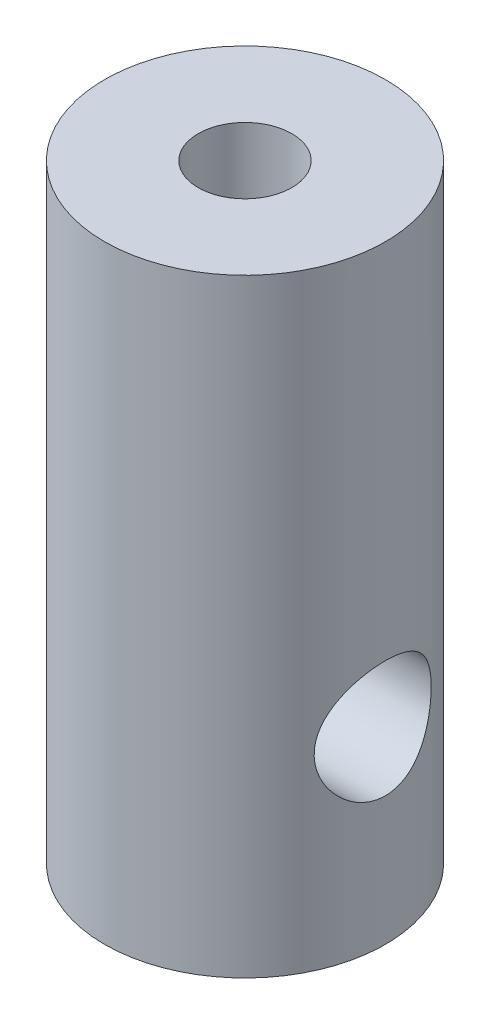
SolidWorks part; units mm, degrees
material "Alliage 1060"
ref_plane "Plan de face" through (0, 0, 0) normal (0, 0, 1) x (1, 0, 0)
ref_plane "Plan de dessus" through (0, 0, 0) normal (0, 1, 0) x (1, 0, 0)
ref_plane "Plan de droite" through (0, 0, 0) normal (1, 0, 0) x (0, 0, -1)
sketch "Esquisse1" plane through (0, 0, 0) normal (0, 1, 0) x (1, 0, 0)
  circle A0 centre (0, 0) radius 3
  dimension "D1" = 6
extrude "Boss.-Extru.1" add sketch "Esquisse1" along normal blind 13
sketch "Esquisse2" plane through (0, 0, 0) normal (0, -1, 0) x (1, 0, 0)
  circle A0 centre (0, 0) radius 1
  dimension "D1" = 2
extrude "Enlèv. mat.-Extru.1" cut sketch "Esquisse2" against normal through all
sketch "Esquisse3" plane through (0, 13, 0) normal (0, 1, 0) x (1, 0, 0)
  line L1 (-1, -3.0804) -> (1, -3.0804)
  line L2 (-1, -3.0804) -> (-1, 3.0804)
  line L3 (-1, 3.0804) -> (1, 3.0804)
  line L4 (1, -3.0804) -> (1, 3.0804)
  line L5 (-1, -3.0804) -> (1, 3.0804) construction
  line L6 (-1, 3.0804) -> (1, -3.0804) construction
  point P0 (0, 0)
  dimension "D1" = 2
extrude "Enlèv. mat.-Extru.2" [suppressed] cut sketch "Esquisse3" against normal blind 2
sketch "Esquisse4" plane through (0, 0, 0) normal (1, 0, 0) x (0, 0, -1)
  line L0 (0, 0) -> (0, 10.3158) construction
  circle A0 centre (0, 4) radius 1.25
  dimension "D1" = 2.5
  dimension "D2" = 4
extrude "Enlèv. mat.-Extru.3" cut sketch "Esquisse4" against normal through all and the other way through all contours A0
